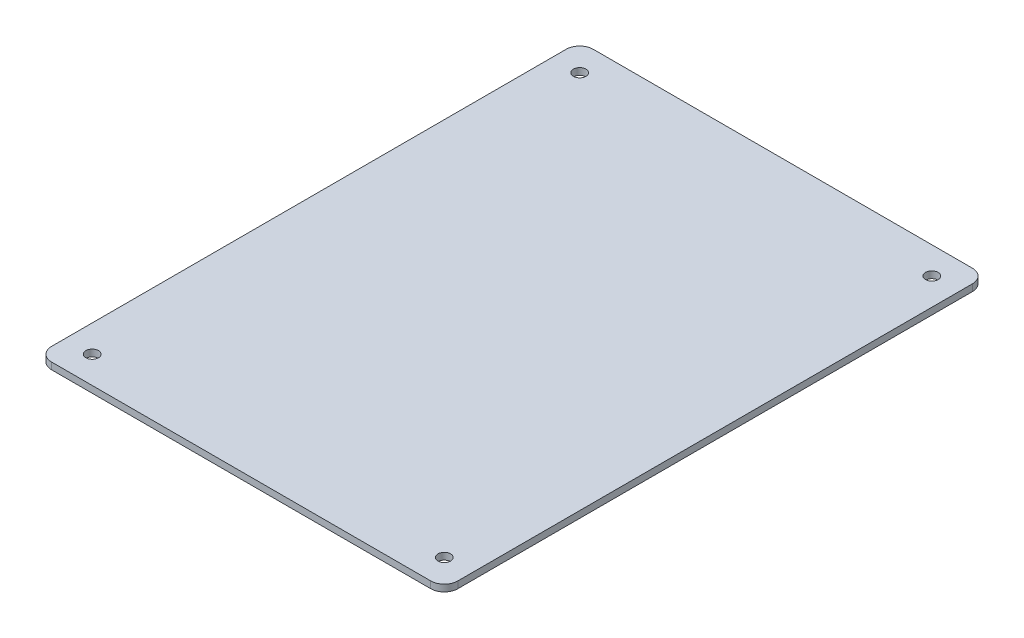
SolidWorks part; units mm, degrees
material "PE High Density"
ref_plane "Front Plane" through (0, 0, 0) normal (0, 0, 1) x (1, 0, 0)
ref_plane "Top Plane" through (0, 0, 0) normal (0, 1, 0) x (1, 0, 0)
ref_plane "Right Plane" through (0, 0, 0) normal (1, 0, 0) x (0, 0, -1)
sketch "Sketch1" plane through (0, 0, 0) normal (0, 1, 0) x (1, 0, 0)
  line L1 (-47.625, 63.5) -> (47.625, 63.5)
  line L2 (-47.625, 63.5) -> (-47.625, -63.5)
  line L3 (-47.625, -63.5) -> (47.625, -63.5)
  line L4 (47.625, 63.5) -> (47.625, -63.5)
  line L5 (-47.625, 63.5) -> (47.625, -63.5) construction
  line L6 (-47.625, -63.5) -> (47.625, 63.5) construction
  point P0 (0, 0)
  dimension "D1" = 95.25
  dimension "D2" = 127
extrude "Boss-Extrude1" add sketch "Sketch1" along normal blind 1.5875
hole_wizard "#4 Clearance Hole1" positions "Sketch3" profile "Sketch4" hole size "#4" standard "Ansi Inch"
sketch "Sketch3" plane through (0, 1.5875, 0) normal (0, 1, 0) x (-1, 0, 0)
  line L1 (41.275, -57.15) -> (-41.275, -57.15) construction
  line L2 (41.275, -57.15) -> (41.275, 57.15) construction
  line L3 (41.275, 57.15) -> (-41.275, 57.15) construction
  line L4 (-41.275, -57.15) -> (-41.275, 57.15) construction
  line L5 (41.275, -57.15) -> (-41.275, 57.15) construction
  line L6 (41.275, 57.15) -> (-41.275, -57.15) construction
  point P0 (41.275, -57.15)
  point P14 (0, 0)
  point P18 (-41.275, -57.15)
  point P20 (-41.275, 57.15)
  point P22 (41.275, 57.15)
  dimension "D1" = 82.55
  dimension "D2" = 114.3
sketch "Sketch4" plane through (-41.275, 1.5875, -57.15) normal (1, 0, 0) x (0, 0, 1)
  line L0 (0, 0) -> (0, 10.5372)
  line L1 (0, 10.5372) -> (1.4732, 9.652)
  line L2 (1.4732, 9.652) -> (1.4732, 0)
  line L5 (1.4732, 0) -> (0, 0)
  line L10 (0, 10.5372) -> (-1.4732, 9.652) construction
  line L11 (0, -6.35) -> (0, 107.95) construction
  dimension "Hole Dia." = 2.9464
  dimension "Hole Depth" = 9.652
  dimension "Drill Angle" = 118
fillet "Fillet1" radius 3.175 4 edges at (-47.625, 0.7937, 63.5) (47.625, 0.7937, 63.5) (47.625, 0.7937, -63.5) (-47.625, 0.7937, -63.5)
